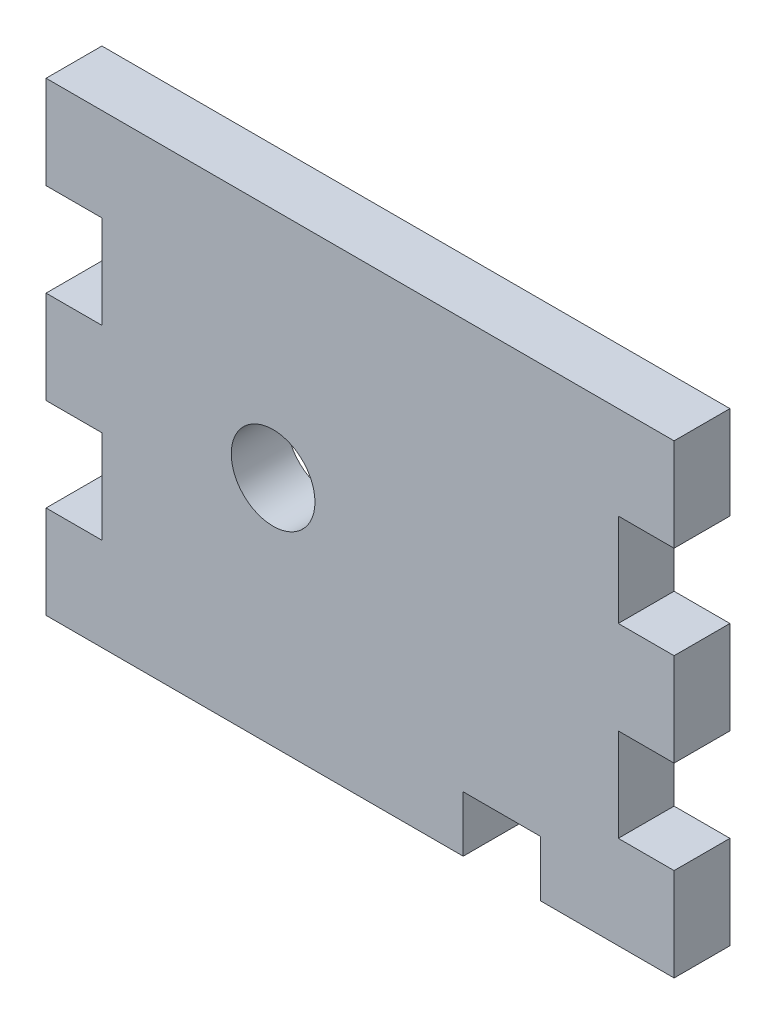
SolidWorks part; units mm, degrees
ref_plane "Front Plane" through (0, 0, 0) normal (0, 0, 1) x (1, 0, 0)
ref_plane "Top Plane" through (0, 0, 0) normal (0, 1, 0) x (1, 0, 0)
ref_plane "Right Plane" through (0, 0, 0) normal (1, 0, 0) x (0, 0, -1)
sketch "Sketch1" plane through (0, 0, 0) normal (0, 0, 1) x (1, 0, 0)
  line L1 (0, 0) -> (171.45, 0)
  line L2 (0, 0) -> (0, 127)
  line L3 (0, 127) -> (171.45, 127)
  line L4 (171.45, 0) -> (171.45, 127)
  dimension "D1" = 127
  dimension "D2" = 171.45
extrude "Boss-Extrude1" add sketch "Sketch1" along normal blind 15.24
sketch "Sketch5" plane through (0, 0, 15.24) normal (0, 0, 1) x (1, 0, 0)
  line L0 (0, 127) -> (0, 0) construction
  line L1 (0, 101.6) -> (15.24, 101.6)
  line L2 (0, 101.6) -> (0, 76.2)
  line L3 (0, 76.2) -> (15.24, 76.2)
  line L4 (15.24, 101.6) -> (15.24, 76.2)
  line L5 (171.45, 0) -> (171.45, 127) construction
  line L6 (0, 50.8) -> (15.24, 50.8)
  line L7 (0, 50.8) -> (0, 25.4)
  line L8 (0, 25.4) -> (15.24, 25.4)
  line L9 (15.24, 50.8) -> (15.24, 25.4)
  line L10 (171.45, 101.6) -> (156.21, 101.6)
  line L11 (171.45, 101.6) -> (171.45, 76.2)
  line L12 (171.45, 76.2) -> (156.21, 76.2)
  line L13 (156.21, 101.6) -> (156.21, 76.2)
  line L14 (15.24, 101.6) -> (15.24, 127) construction
  line L15 (171.45, 50.8) -> (156.21, 50.8)
  line L16 (171.45, 50.8) -> (171.45, 25.4)
  line L17 (171.45, 25.4) -> (156.21, 25.4)
  line L18 (156.21, 50.8) -> (156.21, 25.4)
  line L19 (171.45, 127) -> (0, 127) construction
  line L20 (15.24, 76.2) -> (15.24, 50.8) construction
  line L21 (15.24, 25.4) -> (15.24, 0) construction
  line L22 (0, 0) -> (171.45, 0) construction
  line L23 (156.21, 101.6) -> (156.21, 127) construction
  line L24 (156.21, 76.2) -> (156.21, 50.8) construction
  line L25 (156.21, 25.4) -> (156.21, 0) construction
  dimension "D1" = 15.24
  dimension "D2" = 15.24
sketch "Sketch6" plane through (0, 0, 15.24) normal (0, 0, 1) x (1, 0, 0)
extrude "Cut-Extrude1" cut sketch "Sketch5" against normal blind 15.24
sketch "Sketch7" plane through (0, 0, 15.24) normal (0, 0, 1) x (1, 0, 0)
  line L0 (0, 0) -> (171.45, 0) construction
  line L1 (113.8767, 0) -> (135.0433, 0)
  line L2 (113.8767, 0) -> (113.8767, 15.24)
  line L3 (113.8767, 15.24) -> (135.0433, 15.24)
  line L4 (135.0433, 0) -> (135.0433, 15.24)
  line L5 (113.8767, 15.24) -> (0, 15.24) construction
  line L6 (0, 25.4) -> (0, 0) construction
  line L7 (171.45, 0) -> (171.45, 25.4) construction
  dimension "D3" = 15.24
  dimension "D2" = 36.4067
  dimension "D1" = 21.1667
sketch "Sketch11" plane through (0, 0, 15.24) normal (0, 0, 1) x (1, 0, 0)
  line L0 (171.45, 127) -> (0, 127) construction
  line L1 (0, 76.2) -> (0, 50.8) construction
  circle A0 centre (61.976, 63.5) radius 11.43
  point P4 (0, 63.5)
  dimension "D1" = 22.86
  dimension "D2" = 63.5
  dimension "D3" = 61.976
extrude "Cut-Extrude3" cut sketch "Sketch11" against normal blind 15.24
extrude "Cut-Extrude4" cut sketch "Sketch7" against normal blind 15.24
equation "\"MDF\"= .6"
equation "\"Foamcore\"= .1"
equation "\"GMaterial\"= \"MDF\""
equation "\"D1@Boss-Extrude1\"=\"GMaterial\""
equation "\"D2@Sketch7\"=\"GMaterial\" + 2.5/3"
equation "\"D1@Cut-Extrude1\"=\"GMaterial\""
equation "\"D1@Cut-Extrude3\"=\"GMaterial\""
equation "\"D1@Cut-Extrude4\"=\"GMaterial\""
equation "\"D2@Sketch5\"=\"GMaterial\""
equation "\"D1@Sketch5\"=\"GMaterial\""
equation "\"D3@Sketch7\"=\"GMaterial\""
